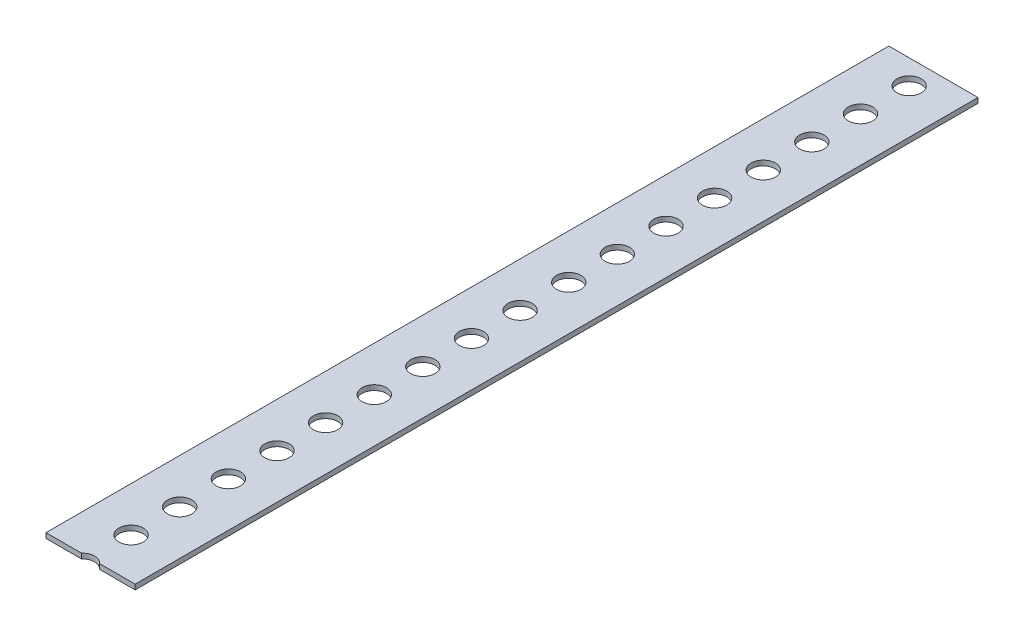
SolidWorks part; units mm, degrees
material "Galvanized Steel"
ref_plane "Front Plane" through (0, 0, 0) normal (0, 0, 1) x (1, 0, 0)
ref_plane "Top Plane" through (0, 0, 0) normal (0, 1, 0) x (1, 0, 0)
ref_plane "Right Plane" through (0, 0, 0) normal (1, 0, 0) x (0, 0, -1)
sketch "Sketch1" plane through (0, 0, 0) normal (0, 1, 0) x (1, 0, 0)
  line L1 (-17.4625, 457.2) -> (17.4625, 457.2) construction
  line L2 (-17.4625, 457.2) -> (-17.4625, -457.2) construction
  line L3 (-17.4625, -457.2) -> (17.4625, -457.2) construction
  line L4 (17.4625, 457.2) -> (17.4625, -457.2) construction
  line L5 (-17.4625, 457.2) -> (17.4625, -457.2) construction
  line L6 (-17.4625, -457.2) -> (17.4625, 457.2) construction
  line L8 (0, -457.2) -> (0, -447.675) construction
  circle A0 centre (0, -447.675) radius 4.7625 construction
  circle A2 centre (0, -428.625) radius 4.7625 construction
  point P0 (0, 0)
  point P13 (0, -387.35)
  point P19 (0, 387.35)
  dimension "D1" = 9.525
  dimension "Length" = 914.4
  dimension "Width (A)" = 34.925
  dimension "D3" = 19.05
  dimension "D4" = 9.525
  dimension "D5" = 69.85
  dimension "D6" = 69.85
sketch "Sketch2" plane through (0, 0, 0) normal (1, 0, 0) x (0, 0, -1)
  line L0 (0, -0.9919) -> (0, 0.9919) construction
  dimension "Thickness" = 1.9837
sketch "Sketch3" plane through (0, 0, 0) normal (0, 1, 0) x (1, 0, 0)
  line L0 (-17.4625, 457.2) -> (17.4625, 457.2) construction
  line L1 (17.4625, 457.2) -> (17.4625, -457.2) construction
  line L2 (-17.4625, -457.2) -> (17.4625, -457.2) construction
  line L3 (-17.4625, 457.2) -> (-17.4625, -457.2) construction
  line L4 (-17.4625, 457.2) -> (17.4625, 457.2)
  line L5 (17.4625, 457.2) -> (17.4625, -457.2)
  line L6 (-17.4625, -457.2) -> (17.4625, -457.2)
  line L7 (-17.4625, 457.2) -> (-17.4625, -457.2)
extrude "Boss-Extrude1" add sketch "Sketch3" against normal up to vertex (0.9919 mm away) and the other way up to vertex (0.9919 mm away) up to point (0, -0.9919, 0) other way up to point (0, 0.9919, 0)
sketch "Sketch4" plane through (0, 0.9919, 0) normal (0, 1, 0) x (1, 0, 0)
  circle A0 centre (0, -447.675) radius 4.7625 construction
  circle A1 centre (0, -447.675) radius 4.7625
extrude "Cut-Extrude1" cut sketch "Sketch4" against normal up to next
pattern_linear "LPattern1" count 53 spacing 19.05 along (0, 0, -1) of "Cut-Extrude1"
sketch "Sketch5" plane through (0, 0, 457.2) normal (0, 0, 1) x (1, 0, 0)
  line L1 (-17.4625, -0.9919) -> (17.4625, -0.9919)
  line L2 (-17.4625, -0.9919) -> (-17.4625, 0.9919)
  line L3 (-17.4625, 0.9919) -> (17.4625, 0.9919)
  line L4 (17.4625, -0.9919) -> (17.4625, 0.9919)
extrude "Cut-Extrude2" cut sketch "Sketch5" against normal blind 584.2
equation "\"D4@Sketch1\"=\"D3@Sketch1\"/2"
equation "\"D3@Sketch1\"=\"D1@Sketch1\"*2"
equation "\"D3@LPattern1\"=\"D3@Sketch1\""
equation "\"D1@LPattern1\"=( \"Length@Sketch1\" / \"D3@Sketch1\" ) + 5"
equation "\"D5@Sketch1\"=\"Width (A)@Sketch1\"*2"
equation "\"D6@Sketch1\"=\"D5@Sketch1\""
